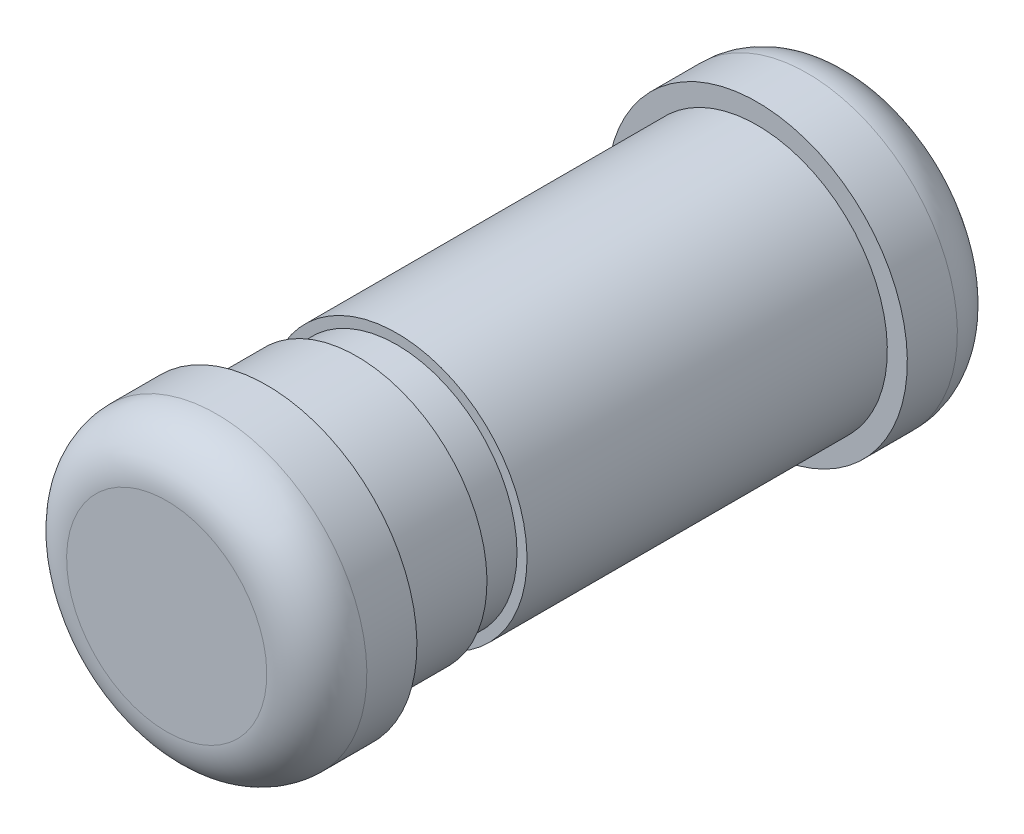
SolidWorks part; units mm, degrees
ref_plane "Front Plane" through (0, 0, 0) normal (0, 0, 1) x (1, 0, 0)
ref_plane "Top Plane" through (0, 0, 0) normal (0, 1, 0) x (1, 0, 0)
ref_plane "Right Plane" through (0, 0, 0) normal (1, 0, 0) x (0, 0, -1)
sketch "Sketch1" plane through (0, 0, 0) normal (1, 0, 0) x (0, 0, -1)
  line L0 (-1.725, 0) -> (1.725, 0) construction
  line L1 (-1.475, -0.75) -> (-1.225, -0.75)
  line L2 (-1.225, -0.75) -> (-1.225, -0.65)
  line L3 (-1.225, -0.65) -> (-0.775, -0.65)
  line L4 (-1.725, -0.5) -> (-1.725, 0)
  line L5 (0, 0) -> (0, -1.1319) construction
  line L6 (1.725, -0.5) -> (1.725, 0)
  line L7 (1.475, -0.75) -> (1.225, -0.75)
  line L8 (1.225, -0.75) -> (1.225, -0.65)
  line L9 (1.225, -0.65) -> (0.775, -0.65)
  line L10 (0.775, -0.65) -> (-0.575, -0.65)
  line L11 (-0.575, -0.65) -> (-0.575, -0.6)
  line L12 (-0.575, -0.6) -> (-0.775, -0.6)
  line L13 (-0.775, -0.6) -> (-0.775, -0.65)
  line L14 (-1.725, 0.6521) -> (1.725, 0.6521) construction
  line L15 (-1.725, 0) -> (-1.725, 0.6521) construction
  line L16 (1.725, 0) -> (1.725, 0.6521) construction
  line L17 (-1.725, 0) -> (1.725, 0)
  arc A0 (-1.725, -0.5) -> (-1.475, -0.75) centre (-1.475, -0.5) ccw
  arc A1 (1.725, -0.5) -> (1.475, -0.75) centre (1.475, -0.5) cw
  point P3 (0, 0)
  point P11 (-1.725, -0.75)
  dimension "D5" = 0.25
  dimension "D1" = 3.45
  dimension "D2" = 0.75
  dimension "D3" = 1.3
  dimension "D4" = 0.5
  dimension "D6" = 2.45
  dimension "D7" = 0.2
  dimension "D8" = 0.45
  dimension "D9" = 0.05
revolve "Revolve1" add sketch "Sketch1" angle 360 about L17
